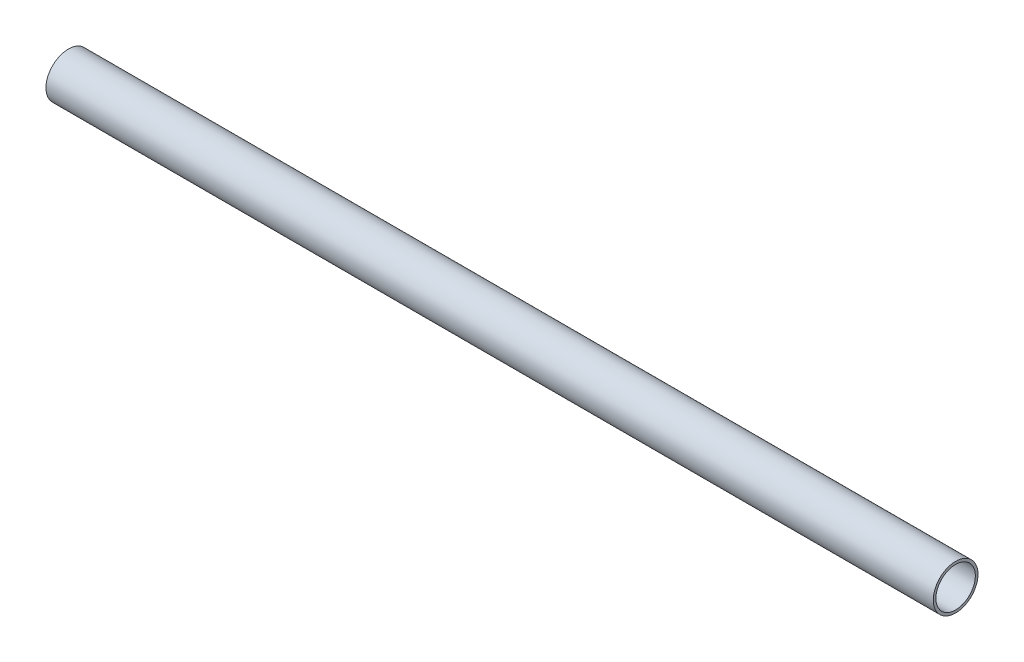
SolidWorks part; units mm, degrees
ref_plane "Front Plane" through (0, 0, 0) normal (0, 0, 1) x (1, 0, 0)
ref_plane "Top Plane" through (0, 0, 0) normal (0, 1, 0) x (1, 0, 0)
ref_plane "Right Plane" through (0, 0, 0) normal (1, 0, 0) x (0, 0, -1)
sketch "Sketch3" plane through (0, 0, 0) normal (0, 0, 1) x (1, 0, 0)
  line L0 (0, 0) -> (355.6, 0)
  dimension "D1" = 355.6
sketch "Sketch4" plane through (0, 0, 0) normal (1, 0, 0) x (0, 0, -1)
  circle A0 centre (0, 0) radius 8.9662
  circle A1 centre (0, 0) radius 7.8994
sweep "Sweep2" add profiles "Sketch4" path "Sketch3"
